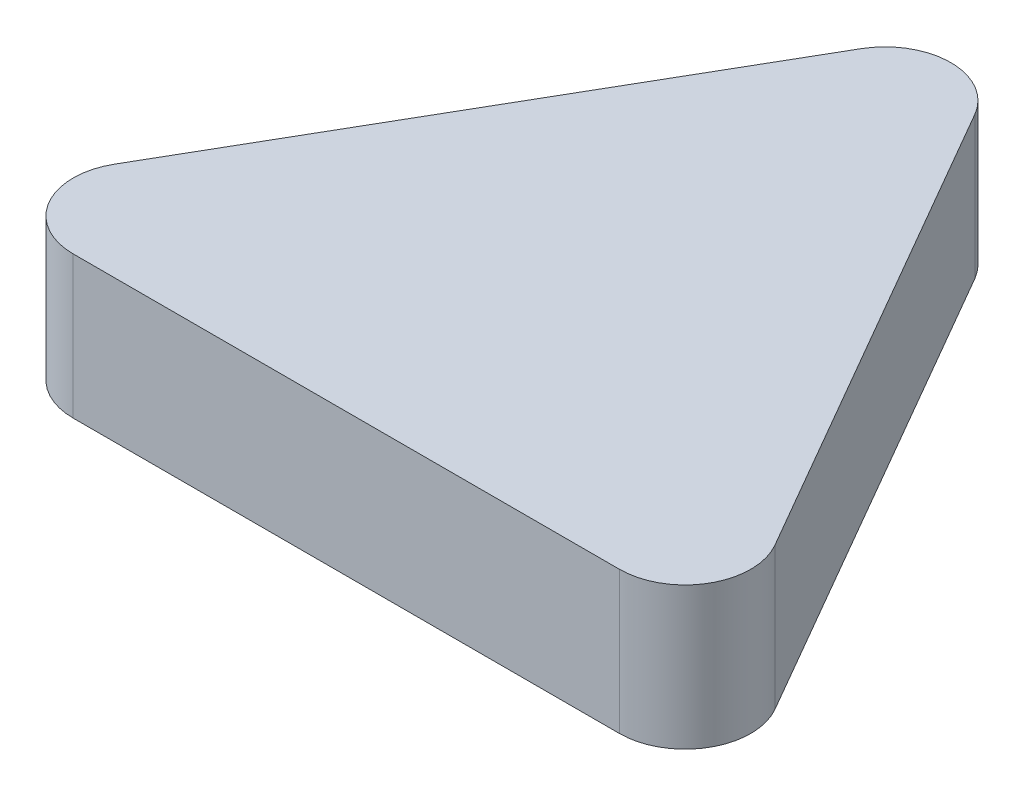
SolidWorks part; units mm, degrees
ref_plane "Front Plane" through (0, 0, 0) normal (0, 0, 1) x (1, 0, 0)
ref_plane "Top Plane" through (0, 0, 0) normal (0, 1, 0) x (1, 0, 0)
ref_plane "Right Plane" through (0, 0, 0) normal (1, 0, 0) x (0, 0, -1)
sketch "Sketch1" plane through (0, 0, 0) normal (0, 1, 0) x (1, 0, 0)
  line L3 (0, 26.9875) -> (0, 0) construction
  line L8 (2.54, 25.521) -> (14.7346, 4.3994)
  line L9 (-2.54, 25.521) -> (-14.7346, 4.3994)
  line L10 (12.1946, 0) -> (-12.1946, 0)
  line L11 (8.6373, 14.9602) -> (-14.7346, 1.4665) construction
  line L13 (14.7346, 1.4665) -> (-8.6373, 14.9602) construction
  arc A0 (-2.54, 25.521) -> (2.54, 25.521) centre (0, 24.0546) cw
  arc A1 (14.7346, 4.3994) -> (12.1946, 0) centre (12.1946, 2.9329) cw
  arc A2 (-12.1946, 0) -> (-14.7346, 4.3994) centre (-12.1946, 2.9329) cw
  point P12 (0, 26.9875)
  point P13 (0, 0)
  dimension "D2" = 26.9875
  dimension "D3" = 5.08
extrude "Boss-Extrude1" add sketch "Sketch1" along normal blind 6.35
sketch "Sketch2" plane through (0, 0, 0) normal (0, -1, 0) x (1, 0, 0)
  line L0 (-13.5797, -3.7327) -> (-1.3852, -24.8543)
  line L1 (1.3852, -24.8543) -> (13.5797, -3.7327)
  line L2 (12.1946, -1.3335) -> (-12.1946, -1.3335)
  line L3 (2.54, -25.521) -> (14.7346, -4.3994)
  line L4 (12.1946, 0) -> (-12.1946, 0)
  line L5 (-14.7346, -4.3994) -> (-2.54, -25.521)
  line L6 (2.54, -25.521) -> (14.7346, -4.3994) construction
  line L7 (12.1946, 0) -> (-12.1946, 0) construction
  line L8 (-14.7346, -4.3994) -> (-2.54, -25.521) construction
  line L9 (-12.1946, -2.9329) -> (0, -9.9735) construction
  line L10 (0, -9.9735) -> (0, -24.0546) construction
  line L11 (12.1946, -2.9329) -> (0, -9.9735) construction
  arc A0 (-12.1946, -1.3335) -> (-13.5797, -3.7327) centre (-12.1946, -2.9329) ccw
  arc A1 (-1.3852, -24.8543) -> (1.3852, -24.8543) centre (0, -24.0546) ccw
  arc A2 (13.5797, -3.7327) -> (12.1946, -1.3335) centre (12.1946, -2.9329) ccw
  arc A3 (-2.54, -25.521) -> (2.54, -25.521) centre (0, -24.0546) ccw
  arc A4 (14.7346, -4.3994) -> (12.1946, 0) centre (12.1946, -2.9329) ccw
  arc A5 (-12.1946, 0) -> (-14.7346, -4.3994) centre (-12.1946, -2.9329) ccw
  arc A6 (-2.54, -25.521) -> (2.54, -25.521) centre (0, -24.0546) ccw construction
  arc A7 (14.7346, -4.3994) -> (12.1946, 0) centre (12.1946, -2.9329) ccw construction
  arc A8 (-12.1946, 0) -> (-14.7346, -4.3994) centre (-12.1946, -2.9329) ccw construction
  dimension "D1" = 0
  dimension "D2" = 1.3335
extrude "Cut-Extrude1" cut sketch "Sketch2" against normal blind 2.413
